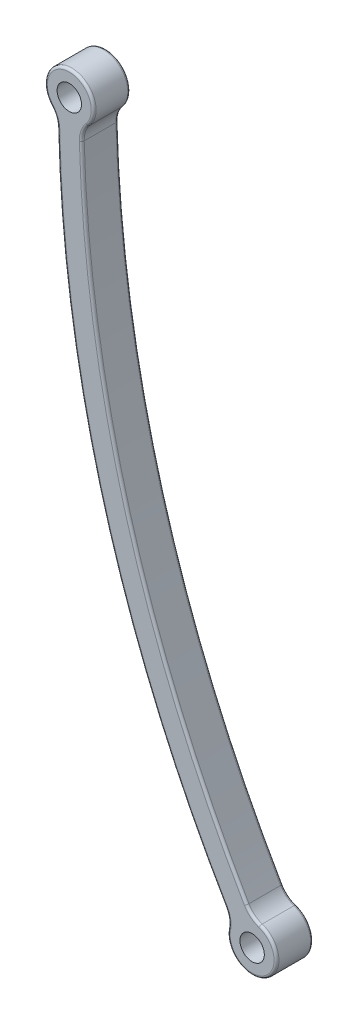
SolidWorks part; units mm, degrees
ref_plane "Front Plane" through (0, 0, 0) normal (0, 0, 1) x (1, 0, 0)
ref_plane "Top Plane" through (0, 0, 0) normal (0, 1, 0) x (1, 0, 0)
ref_plane "Right Plane" through (0, 0, 0) normal (1, 0, 0) x (0, 0, -1)
other "Configuration Table"
sketch "Sketch1" plane through (0, 0, 0) normal (0, 0, 1) x (1, 0, 0)
  line L0 (-19.05, 67.2021) -> (0, 0) construction
  circle A0 centre (0, 0) radius 2.54
  circle A1 centre (-19.05, 67.2021) radius 2.54
  arc A2 (-20.32, 65.0024) -> (-2.1997, 1.27) centre (106.6691, 66.6656) ccw
  arc A3 (-17.78, 65.0024) -> (0, 2.54) centre (109.1976, 67.385) ccw
  circle A4 centre (-19.05, 67.2021) radius 1.27
  circle A5 centre (0, 0) radius 1.27
  dimension "D1" = 2.54
  dimension "D2" = 5.08
  dimension "D5" = 127
  dimension "D6" = 127
  dimension "D7" = 2.54
  dimension "D8" = 2.54
  dimension "D3" = 69.85
  dimension "D4" = 19.05
extrude "Boss-Extrude1" add sketch "Sketch1" along normal mid plane 3.81
fillet "Fillet1" radius 2.54 4 edges at (0, 2.54, 0) (-2.1997, 1.27, 0) (-20.32, 65.0024, 0) (-17.78, 65.0024, 0)
fillet "Fillet2" radius 0.254 16 edges at (-17.6047, 64.7278, 1.905) (-17.6047, 64.7278, -1.905) (-19.068, 69.742, -1.905) (-19.068, 69.742, 1.905) (-20.4765, 64.7502, 1.905) (-20.4765, 64.7502, -1.905) (-15.4944, 31.9513, -1.905) (-15.4944, 31.9513, 1.905) (-2.48, 1.409, 1.905) (-2.48, 1.409, -1.905) (1.2778, -2.1952, -1.905) (1.2778, -2.1952, 1.905) (0.0037, 2.8489, 1.905) (0.0037, 2.8489, -1.905) (-12.9448, 32.5969, 1.905) (-12.9448, 32.5969, -1.905)
scale "Scale1" scale about centroid uniform scaling yes scale factor 1.5
